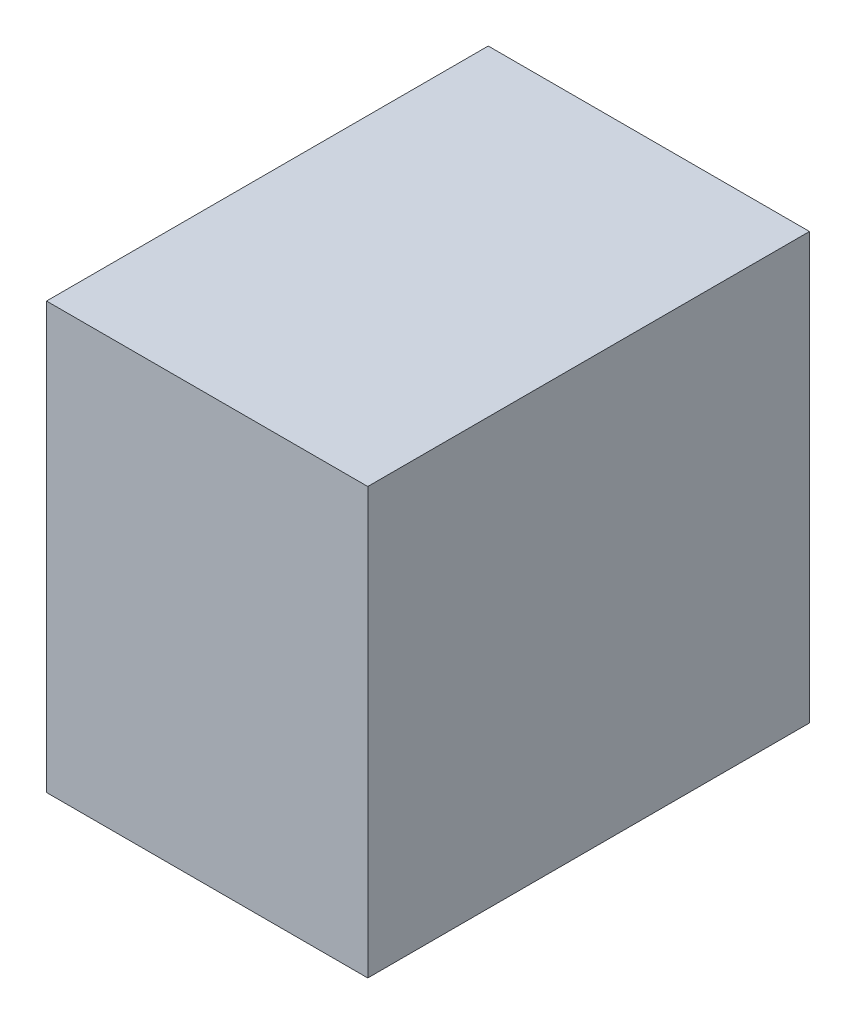
SolidWorks part; units mm, degrees
ref_plane "Front Plane" through (0, 0, 0) normal (0, 0, 1) x (1, 0, 0)
ref_plane "Top Plane" through (0, 0, 0) normal (0, 1, 0) x (1, 0, 0)
ref_plane "Right Plane" through (0, 0, 0) normal (1, 0, 0) x (0, 0, -1)
sketch "Sketch2" plane through (0, 0, 0) normal (0, 1, 0) x (1, 0, 0)
  line L1 (20, -27.5) -> (-20, -27.5)
  line L2 (20, -27.5) -> (20, 27.5)
  line L3 (20, 27.5) -> (-20, 27.5)
  line L4 (-20, -27.5) -> (-20, 27.5)
  line L5 (20, -27.5) -> (-20, 27.5) construction
  line L6 (20, 27.5) -> (-20, -27.5) construction
  point P0 (0, 0)
  dimension "D1" = 40
  dimension "D2" = 55
extrude "Boss-Extrude1" add sketch "Sketch2" along normal blind 53
